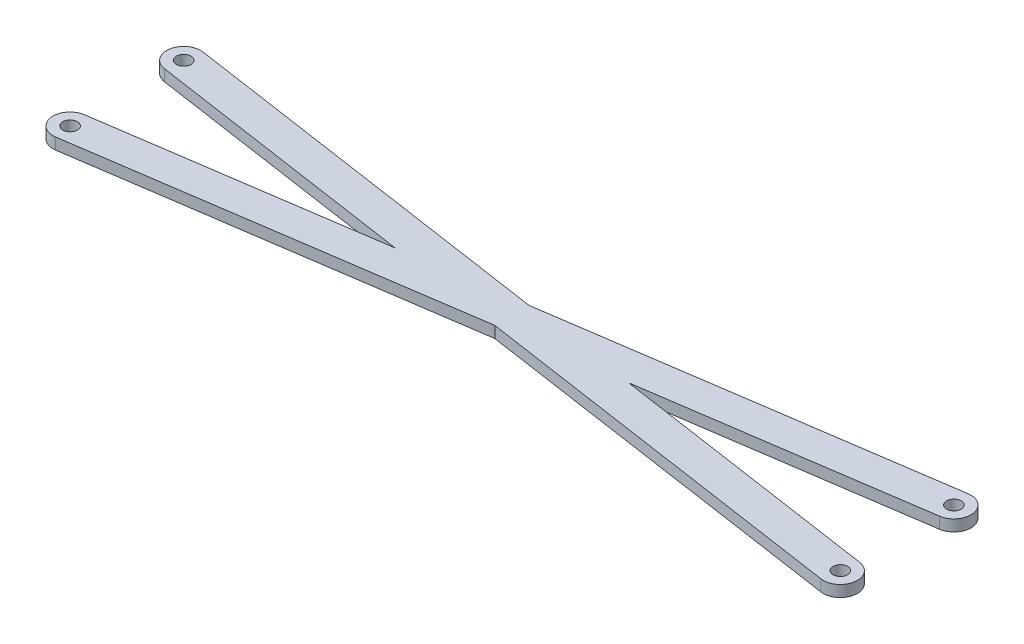
SolidWorks part; units mm, degrees
ref_plane "Front Plane" through (0, 0, 0) normal (0, 0, 1) x (1, 0, 0)
ref_plane "Top Plane" through (0, 0, 0) normal (0, 1, 0) x (1, 0, 0)
ref_plane "Right Plane" through (0, 0, 0) normal (1, 0, 0) x (0, 0, -1)
sketch "Sketch1" plane through (0, 0, 0) normal (0, 1, 0) x (1, 0, 0)
  line L0 (-107.4771, -17.0848) -> (107.7879, 14.6652) construction
  line L1 (-108.1721, -12.3732) -> (-32.4837, -1.2098)
  line L2 (-106.7822, -21.7963) -> (0.1554, -6.0238)
  line L3 (-107.4771, 14.6652) -> (107.7879, -17.0848) construction
  line L4 (-106.7822, 19.3768) -> (0.1554, 3.6043)
  line L5 (-108.1721, 9.9537) -> (-32.4837, -1.2098)
  line L6 (0.1554, -6.0238) -> (107.0929, -21.7963)
  line L7 (32.7944, -1.2098) -> (108.4828, -12.3732)
  line L8 (0.1554, 3.6043) -> (107.0929, 19.3768)
  line L9 (32.7944, -1.2098) -> (108.4828, 9.9537)
  arc A0 (-108.1721, -12.3732) -> (-106.7822, -21.7963) centre (-107.4771, -17.0848) ccw
  arc A1 (108.4828, 9.9537) -> (107.0929, 19.3768) centre (107.7879, 14.6652) ccw
  arc A2 (-106.7822, 19.3768) -> (-108.1721, 9.9537) centre (-107.4771, 14.6652) ccw
  arc A3 (107.0929, -21.7963) -> (108.4828, -12.3732) centre (107.7879, -17.0848) ccw
  point P2 (0, 0)
  point P9 (0.1554, -1.2098)
  point P15 (105.7637, -26.0754)
  point P16 (0, 0)
  point P17 (0, 0)
  point P18 (112.1541, -26.1455)
  dimension "D5" = 4.7625
  dimension "D1" = 215.265
  dimension "D2" = 31.75
  dimension "D3" = 9.525
  dimension "D4" = 9.525
extrude "Boss-Extrude1" add sketch "Sketch1" along normal blind 3.175
sketch "Sketch2" plane through (0, 3.175, 0) normal (0, 1, 0) x (1, 0, 0)
  circle A0 centre (-107.4771, 14.6652) radius 2.032
  circle A1 centre (-107.4771, -17.0848) radius 2.032
  circle A2 centre (107.7879, 14.6652) radius 2.032
  circle A3 centre (107.7879, -17.0848) radius 2.032
  dimension "D1" = 4.064
extrude "Cut-Extrude1" cut sketch "Sketch2" against normal through all
